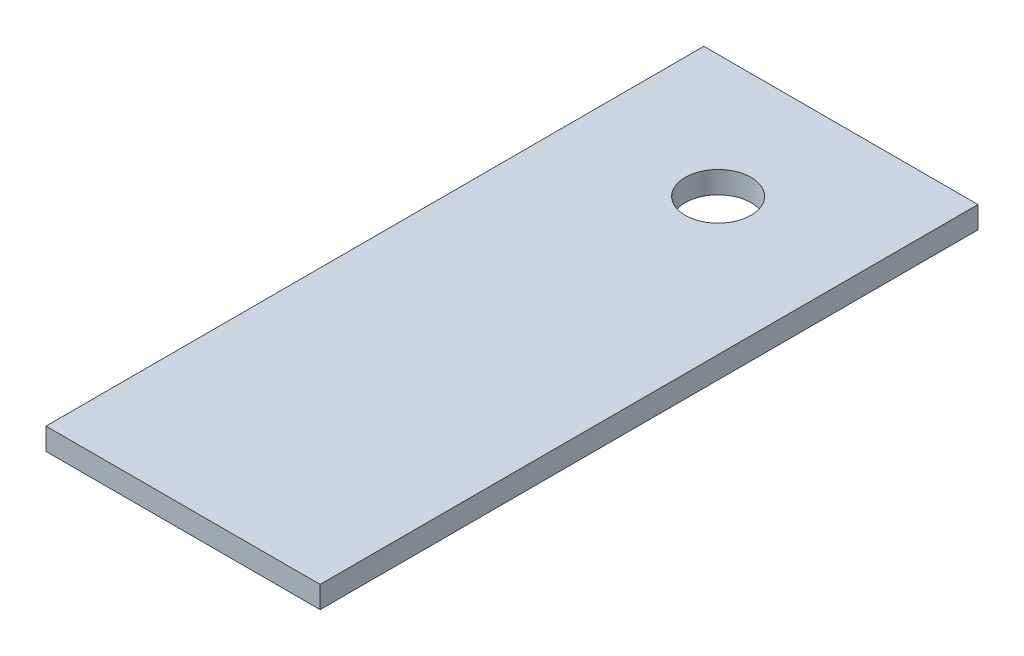
SolidWorks part; units mm, degrees
ref_plane "正面" through (0, 0, 0) normal (0, 0, 1) x (1, 0, 0)
ref_plane "平面" through (0, 0, 0) normal (0, 1, 0) x (1, 0, 0)
ref_plane "右側面" through (0, 0, 0) normal (1, 0, 0) x (0, 0, -1)
sketch "ｽｹｯﾁ1" plane through (0, 0, 0) normal (0, 1, 0) x (1, 0, 0)
  line L1 (-12.5, 30) -> (12.5, 30)
  line L2 (-12.5, 30) -> (-12.5, -30)
  line L3 (-12.5, -30) -> (12.5, -30)
  line L4 (12.5, 30) -> (12.5, -30)
  line L5 (-12.5, 30) -> (12.5, -30) construction
  line L6 (-12.5, -30) -> (12.5, 30) construction
  circle A0 centre (0, 18.8) radius 3
  point P0 (0, 0)
  dimension "D3" = 6
  dimension "D1" = 25
  dimension "D2" = 60
  dimension "D4" = 48.8
extrude "ﾎﾞｽ - 押し出し1" add sketch "ｽｹｯﾁ1" along normal blind 2
